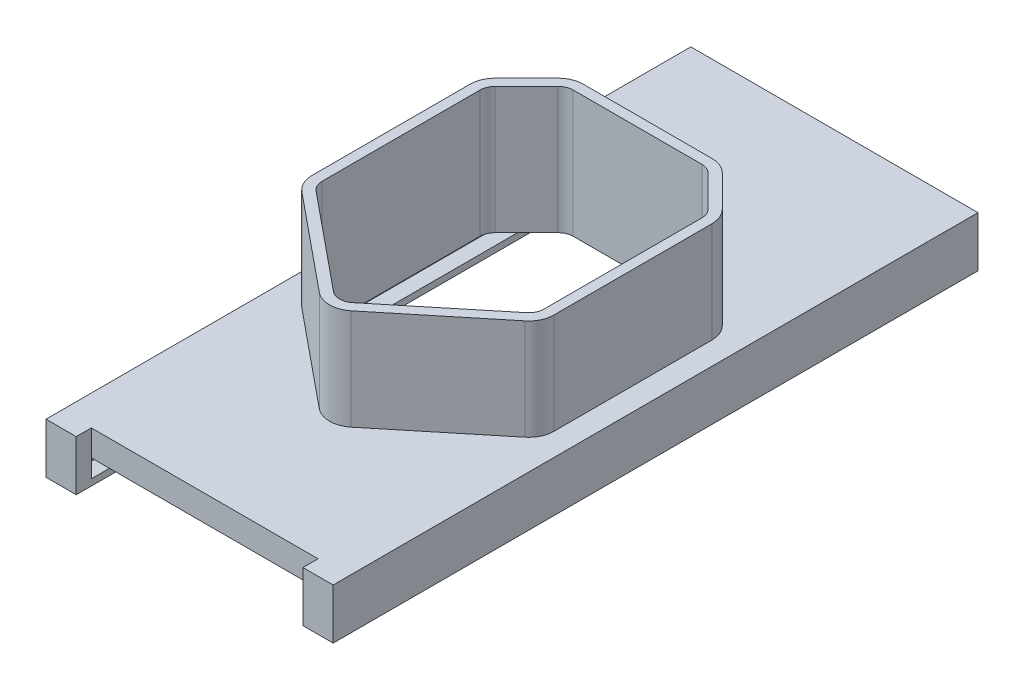
SolidWorks part; units mm, degrees
ref_plane "Front Plane" through (0, 0, 0) normal (0, 0, 1) x (1, 0, 0)
ref_plane "Top Plane" through (0, 0, 0) normal (0, 1, 0) x (1, 0, 0)
ref_plane "Right Plane" through (0, 0, 0) normal (1, 0, 0) x (0, 0, -1)
sketch "Sketch1" plane through (0, 0, 0) normal (0, 1, 0) x (1, 0, 0)
  line L0 (-28.5, 64) -> (28.5, 64)
  line L2 (-25.5, -61) -> (-25.5, 61)
  line L3 (-25.5, 61) -> (25.5, 61)
  line L4 (25.5, -61) -> (25.5, 61)
  line L5 (-25.5, -61) -> (25.5, 61) construction
  line L6 (-25.5, 61) -> (25.5, -61) construction
  line L7 (28.5, -61) -> (28.5, 64)
  line L9 (-28.5, -61) -> (-28.5, 64)
  line L10 (25.5, -61) -> (28.5, -61)
  line L11 (-28.5, -61) -> (-25.5, -61)
  line L12 (0, 64) -> (0, 38.6023) construction
  point P0 (0, 0)
  dimension "D1" = 3
  dimension "D2" = 51
  dimension "D3" = 122
  dimension "D4" = 125
  dimension "D5" = 3
extrude "Boss-Extrude1" add sketch "Sketch1" along normal blind 10 contours L2 L3 L4 L10 L7 L0 L9 L11
sketch "Sketch2" plane through (0, 0, 0) normal (0, -1, 0) x (1, 0, 0)
  line L0 (-25.5, 61) -> (-22.5, 61)
  line L1 (-22.5, 61) -> (-22.5, -61)
  line L2 (-25.5, -61) -> (25.5, -61) construction
  line L3 (-22.5, -61) -> (-25.5, -61)
  line L4 (-25.5, -61) -> (-25.5, 61)
  line L5 (25.5, 61) -> (22.5, 61)
  line L6 (22.5, 61) -> (22.5, -61)
  line L7 (22.5, -61) -> (25.5, -61)
  line L8 (25.5, 61) -> (25.5, -61) construction
  line L9 (25.5, -61) -> (25.5, 61)
  dimension "D1" = 45
extrude "Boss-Extrude2" add sketch "Sketch2" against normal blind 1.25
sketch "Sketch3" plane through (0, 0, 61) normal (0, 0, 1) x (1, 0, 0)
  line L0 (-25.5, 10) -> (25.5, 10) construction
  line L1 (-28.5, 0) -> (-22.5, 0)
  line L2 (-28.5, 0) -> (-28.5, 10)
  line L3 (-28.5, 10) -> (-22.5, 10)
  line L4 (-22.5, 0) -> (-22.5, 10)
  line L5 (-22.5, 1.25) -> (-22.5, 0) construction
  line L6 (28.5, 0) -> (22.5, 0)
  line L7 (28.5, 0) -> (28.5, 10)
  line L8 (28.5, 10) -> (22.5, 10)
  line L9 (22.5, 0) -> (22.5, 10)
  line L10 (22.5, 1.25) -> (22.5, 0) construction
extrude "Boss-Extrude3" add sketch "Sketch3" along normal blind 3
sketch "Sketch4" plane through (-25.5, 0, 0) normal (1, 0, 0) x (0, 0, -1)
  line L0 (61, 10) -> (61, 1.25) construction
  line L1 (-61, 10) -> (61, 10)
  line L2 (-61, 10) -> (-61, 4.85)
  line L3 (-61, 4.85) -> (61, 4.85)
  line L4 (61, 10) -> (61, 4.85)
  line L5 (-61, 1.25) -> (61, 1.25) construction
  dimension "D1" = 3.6
extrude "Boss-Extrude4" add sketch "Sketch4" along normal blind 52
sketch "Sketch5" plane through (0, 10, 0) normal (0, 1, 0) x (1, 0, 0)
  line L0 (-22, 15.6679) -> (-22, -15.6679)
  line L1 (-20.8997, -17.9897) -> (-1.8997, -33.5352)
  line L2 (1.8997, -33.5352) -> (20.8997, -17.9897)
  line L3 (22, -15.6679) -> (22, 15.6679)
  line L4 (-21.1213, 17.7892) -> (-14.8787, 24.0318)
  line L5 (-12.7574, 24.9105) -> (12.7574, 24.9105)
  line L6 (14.8787, 24.0318) -> (21.1213, 17.7892)
  line L7 (0, 22.8296) -> (0, -5.4041) construction
  line L8 (0, 24.9105) -> (0, 27.5719) construction
  arc A0 (-22, 15.6679) -> (-21.1213, 17.7892) centre (-19, 15.6679) cw
  arc A1 (-14.8787, 24.0318) -> (-12.7574, 24.9105) centre (-12.7574, 21.9105) cw
  arc A2 (12.7574, 24.9105) -> (14.8787, 24.0318) centre (12.7574, 21.9105) cw
  arc A3 (22, 15.6679) -> (21.1213, 17.7892) centre (19, 15.6679) ccw
  arc A4 (20.8997, -17.9897) -> (22, -15.6679) centre (19, -15.6679) ccw
  arc A5 (-22, -15.6679) -> (-20.8997, -17.9897) centre (-19, -15.6679) ccw
  arc A6 (-1.8997, -33.5352) -> (1.8997, -33.5352) centre (0, -31.2133) ccw
  point P13 (22, 0)
  point P16 (-22, 16.9105)
  point P19 (-14, 24.9105)
  point P22 (14, 24.9105)
  point P25 (22, 16.9105)
  point P28 (22, -17.0895)
  point P31 (-22, -17.0895)
  point P34 (0, -35.0895)
  dimension "D6" = 3
  dimension "D1" = 34
  dimension "D2" = 8
  dimension "D3" = 18
  dimension "D4" = 28
  dimension "D5" = 44
extrude "Cut-Extrude1" cut sketch "Sketch5" against normal blind 52
sketch "Sketch6" plane through (0, 10, 0) normal (0, 1, 0) x (1, 0, 0)
  line L0 (-22.1662, -19.5376) -> (-3.1662, -35.0831)
  line L1 (3.1662, -35.0831) -> (22.1662, -19.5376)
  line L2 (24, -15.6679) -> (24, 15.6679)
  line L3 (22.5355, 19.2034) -> (16.2929, 25.446)
  line L4 (12.7574, 26.9105) -> (-12.7574, 26.9105)
  line L5 (-16.2929, 25.446) -> (-22.5355, 19.2034)
  line L6 (-24, 15.6679) -> (-24, -15.6679)
  line L7 (-20.8997, -17.9897) -> (-1.8997, -33.5352)
  line L8 (-22, 15.6679) -> (-22, -15.6679)
  line L9 (-14.8787, 24.0318) -> (-21.1213, 17.7892)
  line L10 (12.7574, 24.9105) -> (-12.7574, 24.9105)
  line L11 (21.1213, 17.7892) -> (14.8787, 24.0318)
  line L12 (22, -15.6679) -> (22, 15.6679)
  line L13 (1.8997, -33.5352) -> (20.8997, -17.9897)
  line L14 (-20.8997, -17.9897) -> (-1.8997, -33.5352)
  line L15 (-22, 15.6679) -> (-22, -15.6679)
  line L16 (-14.8787, 24.0318) -> (-21.1213, 17.7892)
  line L17 (12.7574, 24.9105) -> (-12.7574, 24.9105)
  line L18 (21.1213, 17.7892) -> (14.8787, 24.0318)
  line L19 (22, -15.6679) -> (22, 15.6679)
  line L20 (1.8997, -33.5352) -> (20.8997, -17.9897)
  arc A0 (-3.1662, -35.0831) -> (3.1662, -35.0831) centre (0, -31.2133) ccw
  arc A1 (22.1662, -19.5376) -> (24, -15.6679) centre (19, -15.6679) ccw
  arc A2 (24, 15.6679) -> (22.5355, 19.2034) centre (19, 15.6679) ccw
  arc A3 (16.2929, 25.446) -> (12.7574, 26.9105) centre (12.7574, 21.9105) ccw
  arc A4 (-12.7574, 26.9105) -> (-16.2929, 25.446) centre (-12.7574, 21.9105) ccw
  arc A5 (-22.5355, 19.2034) -> (-24, 15.6679) centre (-19, 15.6679) ccw
  arc A6 (-24, -15.6679) -> (-22.1662, -19.5376) centre (-19, -15.6679) ccw
  arc A7 (-22, -15.6679) -> (-20.8997, -17.9897) centre (-19, -15.6679) ccw
  arc A8 (-21.1213, 17.7892) -> (-22, 15.6679) centre (-19, 15.6679) ccw
  arc A9 (-12.7574, 24.9105) -> (-14.8787, 24.0318) centre (-12.7574, 21.9105) ccw
  arc A10 (14.8787, 24.0318) -> (12.7574, 24.9105) centre (12.7574, 21.9105) ccw
  arc A11 (22, 15.6679) -> (21.1213, 17.7892) centre (19, 15.6679) ccw
  arc A12 (20.8997, -17.9897) -> (22, -15.6679) centre (19, -15.6679) ccw
  arc A13 (-1.8997, -33.5352) -> (1.8997, -33.5352) centre (0, -31.2133) ccw
  arc A14 (-22, -15.6679) -> (-20.8997, -17.9897) centre (-19, -15.6679) ccw
  arc A15 (-21.1213, 17.7892) -> (-22, 15.6679) centre (-19, 15.6679) ccw
  arc A16 (-12.7574, 24.9105) -> (-14.8787, 24.0318) centre (-12.7574, 21.9105) ccw
  arc A17 (14.8787, 24.0318) -> (12.7574, 24.9105) centre (12.7574, 21.9105) ccw
  arc A18 (22, 15.6679) -> (21.1213, 17.7892) centre (19, 15.6679) ccw
  arc A19 (20.8997, -17.9897) -> (22, -15.6679) centre (19, -15.6679) ccw
  arc A20 (-1.8997, -33.5352) -> (1.8997, -33.5352) centre (0, -31.2133) ccw
  dimension "D1" = 0
  dimension "D2" = 2
extrude "Boss-Extrude6" add sketch "Sketch6" along normal blind 20
